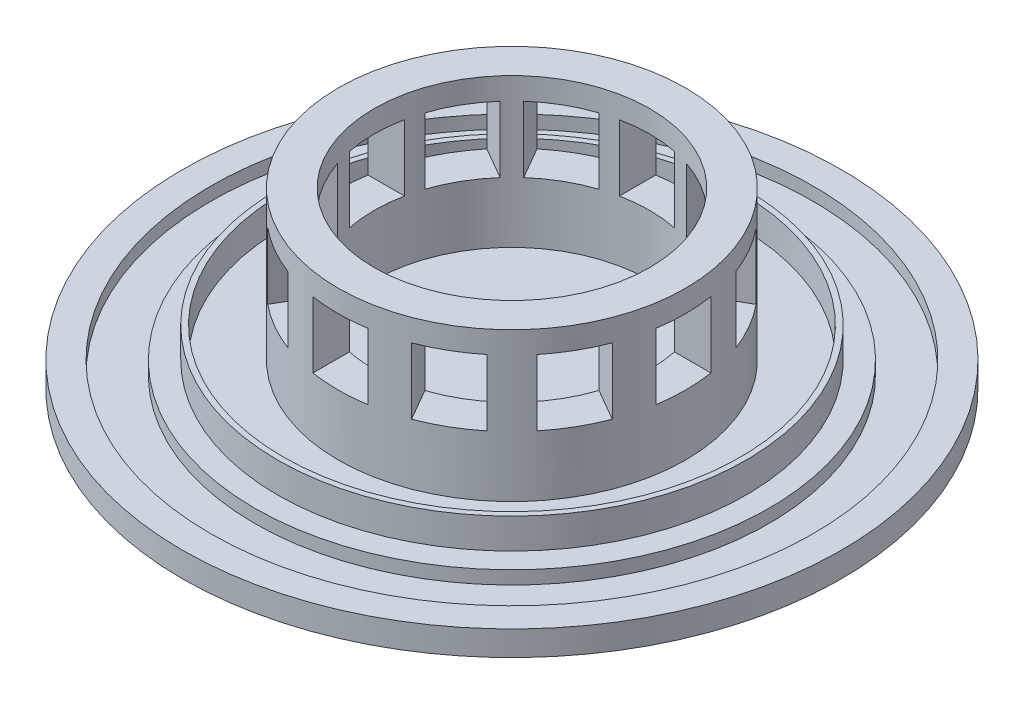
SolidWorks part; units mm, degrees
ref_plane "Front Plane" through (0, 0, 0) normal (0, 0, 1) x (1, 0, 0)
ref_plane "Top Plane" through (0, 0, 0) normal (0, 1, 0) x (1, 0, 0)
ref_plane "Right Plane" through (0, 0, 0) normal (1, 0, 0) x (0, 0, -1)
sketch "Sketch3" plane through (0, 0, 0) normal (1, 0, 0) x (0, 0, -1)
  line L0 (-212.5, 8.0703) -> (-212.5, 35.5532)
  line L1 (-299, 8.0703) -> (-273.25, 8.0703)
  line L2 (-299, 8.0703) -> (-299, -14.4468)
  line L3 (-299, -14.4468) -> (-207.5, -14.4468)
  line L5 (-273.25, 8.0703) -> (-273.25, -3.9297)
  line L6 (-273.25, -3.9297) -> (-233.25, -3.9297)
  line L7 (-212.5, 35.5532) -> (-207.5, 35.5532)
  line L9 (-233.25, -3.9297) -> (-233.25, 8.0703)
  line L10 (-233.25, 8.0703) -> (-212.5, 8.0703)
  line L11 (-253.25, 0) -> (-253.25, -22.5537) construction
  line L12 (0, 120.738) -> (0, -95.9334) construction
  line L13 (-207.5, 35.5532) -> (-207.5, 8.0703)
  line L15 (-207.5, 8.0703) -> (0, 8.0703)
  line L16 (0, 8.0703) -> (0, -14.4468)
  line L17 (0, -14.4468) -> (-207.5, -14.4468)
  point P7 (-210, 35.5532)
  point P14 (-253.25, -14.4468)
  point P16 (-253.25, -3.9297)
  dimension "D2" = 50
  dimension "D3" = 91.5
  dimension "D4" = 5
  dimension "D6" = 12
  dimension "D7" = 40
  dimension "D8" = 12
revolve "Revolve1" add sketch "Sketch3" angle 360 about L12
sketch "Sketch4" plane through (0, 8.0703, 0) normal (0, 1, 0) x (1, 0, 0)
  circle A0 centre (0, 0) radius 125
  circle A1 centre (0, 0) radius 157.5
  dimension "D1" = 250
  dimension "D2" = 315
extrude "Boss-Extrude1" add sketch "Sketch4" along normal blind 135
sketch "Sketch5" plane through (0, 0, 0) normal (0, 0, 1) x (1, 0, 0)
  line L0 (125, 143.0703) -> (-125, 143.0703) construction
  line L1 (-25, 123.0703) -> (25, 123.0703)
  line L2 (-25, 123.0703) -> (-25, 63.0703)
  line L3 (-25, 63.0703) -> (25, 63.0703)
  line L4 (25, 123.0703) -> (25, 63.0703)
  line L5 (-25, 123.0703) -> (25, 63.0703) construction
  line L6 (-25, 63.0703) -> (25, 123.0703) construction
  point P0 (0, 93.0703)
  dimension "D1" = 60
  dimension "D2" = 50
  dimension "D3" = 50
extrude "Cut-Extrude1" cut sketch "Sketch5" against normal through all both and the other way through all
pattern_circular "CirPattern1" count 12 over 360 about axis through (0, 0, 0) along (0, 1, 0) of "Cut-Extrude1"
